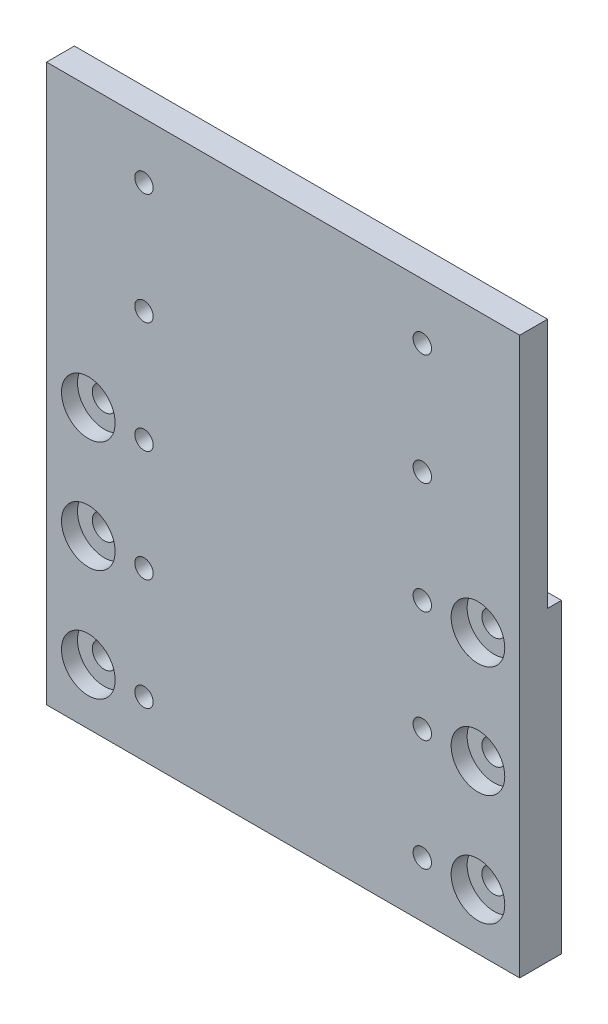
SolidWorks part; units mm, degrees
ref_plane "Front Plane" through (0, 0, 0) normal (0, 0, 1) x (1, 0, 0)
ref_plane "Top Plane" through (0, 0, 0) normal (0, 1, 0) x (1, 0, 0)
ref_plane "Right Plane" through (0, 0, 0) normal (1, 0, 0) x (0, 0, -1)
sketch "Sketch1" plane through (0, 0, 0) normal (0, 0, 1) x (1, 0, 0)
  line L1 (53.975, -63.5) -> (-53.975, -63.5)
  line L2 (53.975, -63.5) -> (53.975, 63.5)
  line L3 (53.975, 63.5) -> (-53.975, 63.5)
  line L4 (-53.975, -63.5) -> (-53.975, 63.5)
  line L5 (53.975, -63.5) -> (-53.975, 63.5) construction
  line L6 (53.975, 63.5) -> (-53.975, -63.5) construction
  point P0 (0, 0)
  dimension "D1" = 107.95
  dimension "D2" = 127
extrude "Extrude1" add sketch "Sketch1" along normal blind 9.525
sketch "Sketch10" plane through (0, 0, 9.525) normal (0, 0, 1) x (1, 0, 0)
  line L0 (0, -63.5) -> (0, 63.5)
  line L1 (-53.975, -63.5) -> (53.975, -63.5) construction
  line L2 (53.975, 63.5) -> (-53.975, 63.5) construction
  line L3 (0, 63.5) -> (0, 0)
  line L4 (0, 0) -> (85.2515, 0)
  line L5 (0, 0) -> (-70.116, 0)
hole_wizard "CBORE for M5 Hex Head Cap Screw2" positions "3DSketch2" profile "Sketch11" counterbore size "M5" standard "Ansi Metric" end condition through all
sketch3d "3DSketch2"
  line L0 (-53.975, -63.5, 9.525) -> (53.975, -63.5, 9.525) construction
  line L1 (0, -63.5, 9.525) -> (0, 63.5, 9.525) construction
  point P0 (-44.45, -50.8, 9.525)
  dimension "D1" = 12.7
  dimension "D2" = 44.45
sketch "Sketch11" plane through (-44.45, -50.8, 9.525) normal (1, 0, 0) x (0, -1, 0)
  line L0 (0, 0) -> (0, 9.525)
  line L1 (0, 9.525) -> (2.75, 9.525)
  line L3 (2.75, 9.525) -> (2.75, 3.65)
  line L4 (2.75, 3.65) -> (6.12, 3.65)
  line L5 (6.12, 3.65) -> (6.12, 0)
  line L7 (6.12, 0) -> (0, 0)
  line L11 (0, -6.35) -> (0, 107.95) construction
  dimension "Thru Hole Dia." = 5.5
  dimension "Thru Hole Depth" = 9.525
  dimension "C'Bore Dia." = 12.24
  dimension "C'Bore Depth" = 3.65
sketch "Sketch12" plane through (0, 0, 9.525) normal (0, 0, 1) x (1, 0, 0)
  line L0 (-44.45, -50.8) -> (-44.45, 36.1848) construction
pattern_linear "LPattern5" count 3 spacing 25.4 along (0, 1, 0) of "CBORE for M5 Hex Head Cap Screw2"
sketch3d "3DSketch3"
  line L0 (-44.45, -50.8, 9.525) -> (61.2634, -50.8, 9.525) construction
pattern_linear "LPattern6" count 2 spacing 88.9 along (1, 0, 0) of "LPattern5", "CBORE for M5 Hex Head Cap Screw2"
hole_wizard "M5x0.8 Tapped Hole1" positions "3DSketch5" profile "Sketch15" tap size "M5x0.8" standard "Ansi Metric" end condition through all
sketch3d "3DSketch5"
  line L0 (0, -63.5, 9.525) -> (0, 63.5, 9.525) construction
  line L1 (-53.975, -63.5, 9.525) -> (53.975, -63.5, 9.525) construction
  point P0 (-31.75, -50.8, 9.525)
  dimension "D1" = 31.75
  dimension "D2" = 12.7
sketch "Sketch15" plane through (-31.75, -50.8, 9.525) normal (1, 0, 0) x (0, -1, 0)
  line L0 (0, 0) -> (0, 9.525)
  line L1 (0, 9.525) -> (2.1, 9.525)
  line L2 (2.1, 9.525) -> (2.1, 0)
  line L5 (2.1, 0) -> (0, 0)
  line L11 (0, -6.35) -> (0, 107.95) construction
  dimension "Thread Major Dia." = 4.2
  dimension "Thru Tap Drill Depth" = 9.525
sketch3d "3DSketch6"
  line L0 (-31.75, -50.8, 9.525) -> (-31.75, 72.4159, 9.525) construction
  line L1 (-31.75, -50.8, 0) -> (-31.75, -50.8, 9.525) construction
  line L2 (-44.45, -50.8, 9.525) -> (61.2634, -50.8, 9.525) construction
pattern_linear "LPattern7" count 5 spacing 25.4 along (0, 1, 0) of "M5x0.8 Tapped Hole1"
sketch3d "3DSketch7"
  line L0 (-31.75, 50.8, 9.525) -> (66.6286, 50.8, 9.525) construction
  line L1 (-31.75, 50.8, 0) -> (-31.75, 50.8, 9.525) construction
  line L2 (-31.75, -50.8, 9.525) -> (-31.75, 72.4159, 9.525) construction
pattern_linear "LPattern8" count 2 spacing 63.5 along (1, 0, 0) of "LPattern7", "M5x0.8 Tapped Hole1"
sketch "Sketch16" plane through (0, 0, 0) normal (0, 0, -1) x (-1, 0, 0)
  line L0 (53.975, 63.5) -> (53.975, -63.5) construction
  line L1 (-53.975, 63.5) -> (53.975, 63.5)
  line L2 (-53.975, 63.5) -> (-53.975, 6.35)
  line L3 (-53.975, 6.35) -> (53.975, 6.35)
  line L4 (53.975, 63.5) -> (53.975, 6.35)
  dimension "D1" = 57.15
extrude "Extrude2" cut sketch "Sketch16" against normal blind 3.175
